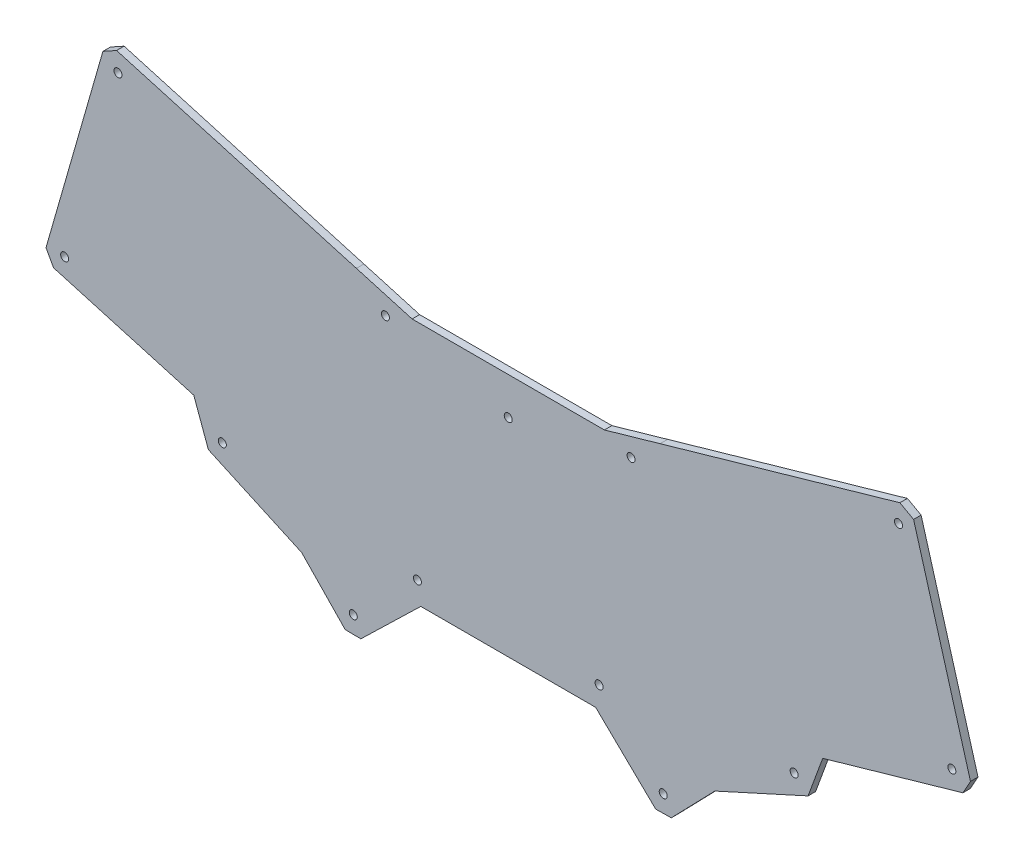
SolidWorks part; units mm, degrees
ref_plane "Plan de face" through (0, 0, 0) normal (0, 0, 1) x (1, 0, 0)
ref_plane "Plan de dessus" through (0, 0, 0) normal (0, 1, 0) x (1, 0, 0)
ref_plane "Plan de droite" through (0, 0, 0) normal (1, 0, 0) x (0, 0, -1)
sketch "Esquisse1" plane through (0, 0, 0) normal (0, 0, 1) x (1, 0, 0)
  line L0 (-121.6461, -32.0475) -> (-108.1875, -28.1884) construction
  line L1 (-108.1875, -28.1884) -> (-104.3283, -41.647) construction
  line L2 (-104.3283, -41.647) -> (-117.7869, -45.5062) construction
  line L3 (-117.7869, -45.5062) -> (-121.6461, -32.0475) construction
  line L4 (-100.1763, -37.9855) -> (-104.0355, -24.5269) construction
  line L5 (-104.0355, -24.5269) -> (-90.5769, -20.6677) construction
  line L6 (-90.5769, -20.6677) -> (-86.7177, -34.1263) construction
  line L7 (-86.7177, -34.1263) -> (-100.1763, -37.9855) construction
  line L8 (-82.5657, -30.4649) -> (-86.4249, -17.0063) construction
  line L9 (-86.4249, -17.0063) -> (-72.9663, -13.1471) construction
  line L10 (-72.9663, -13.1471) -> (-69.1071, -26.6057) construction
  line L11 (-69.1071, -26.6057) -> (-82.5657, -30.4649) construction
  line L12 (-63.6458, -27.5106) -> (-67.505, -14.0519) construction
  line L13 (-67.505, -14.0519) -> (-54.0463, -10.1927) construction
  line L14 (-54.0463, -10.1927) -> (-50.1872, -23.6514) construction
  line L15 (-50.1872, -23.6514) -> (-63.6458, -27.5106) construction
  line L16 (-44.0711, -26.8394) -> (-47.9303, -13.3808) construction
  line L17 (-47.9303, -13.3808) -> (-34.4717, -9.5216) construction
  line L18 (-34.4717, -9.5216) -> (-30.6125, -22.9802) construction
  line L19 (-30.6125, -22.9802) -> (-44.0711, -26.8394) construction
  line L20 (-25.8054, -21.6018) -> (-29.6646, -8.1432) construction
  line L21 (-29.6646, -8.1432) -> (-16.206, -4.284) construction
  line L22 (-16.206, -4.284) -> (-12.3468, -17.7426) construction
  line L23 (-12.3468, -17.7426) -> (-25.8054, -21.6018) construction
  line L24 (-116.4086, -50.3128) -> (-102.95, -46.4536) construction
  line L25 (-102.95, -46.4536) -> (-99.0908, -59.9122) construction
  line L26 (-99.0908, -59.9122) -> (-112.5494, -63.7714) construction
  line L27 (-112.5494, -63.7714) -> (-116.4086, -50.3128) construction
  line L28 (-98.798, -42.7922) -> (-85.3394, -38.933) construction
  line L29 (-85.3394, -38.933) -> (-81.4802, -52.3916) construction
  line L30 (-81.4802, -52.3916) -> (-94.9388, -56.2508) construction
  line L31 (-94.9388, -56.2508) -> (-98.798, -42.7922) construction
  line L32 (-81.1874, -35.2715) -> (-67.7288, -31.4123) construction
  line L33 (-67.7288, -31.4123) -> (-63.8696, -44.8709) construction
  line L34 (-63.8696, -44.8709) -> (-77.3282, -48.7301) construction
  line L35 (-77.3282, -48.7301) -> (-81.1874, -35.2715) construction
  line L36 (-62.2675, -32.3172) -> (-48.8089, -28.458) construction
  line L37 (-48.8089, -28.458) -> (-44.9497, -41.9166) construction
  line L38 (-44.9497, -41.9166) -> (-58.4083, -45.7758) construction
  line L39 (-58.4083, -45.7758) -> (-62.2675, -32.3172) construction
  line L40 (-42.6928, -31.646) -> (-29.2342, -27.7869) construction
  line L41 (-29.2342, -27.7869) -> (-25.375, -41.2455) construction
  line L42 (-25.375, -41.2455) -> (-38.8336, -45.1047) construction
  line L43 (-38.8336, -45.1047) -> (-42.6928, -31.646) construction
  line L44 (-24.4271, -26.4084) -> (-10.9685, -22.5492) construction
  line L45 (-10.9685, -22.5492) -> (-7.1093, -36.0078) construction
  line L46 (-7.1093, -36.0078) -> (-20.5679, -39.867) construction
  line L47 (-20.5679, -39.867) -> (-24.4271, -26.4084) construction
  line L48 (-19.1896, -44.6737) -> (-5.731, -40.8145) construction
  line L49 (-5.731, -40.8145) -> (-1.8718, -54.2731) construction
  line L50 (-1.8718, -54.2731) -> (-15.3304, -58.1323) construction
  line L51 (-15.3304, -58.1323) -> (-19.1896, -44.6737) construction
  line L52 (-37.4554, -49.9113) -> (-23.9967, -46.0521) construction
  line L53 (-23.9967, -46.0521) -> (-20.1376, -59.5107) construction
  line L54 (-20.1376, -59.5107) -> (-33.5962, -63.3699) construction
  line L55 (-33.5962, -63.3699) -> (-37.4554, -49.9113) construction
  line L56 (-57.03, -50.5825) -> (-43.5714, -46.7233) construction
  line L57 (-43.5714, -46.7233) -> (-39.7122, -60.1819) construction
  line L58 (-39.7122, -60.1819) -> (-53.1708, -64.0411) construction
  line L59 (-53.1708, -64.0411) -> (-57.03, -50.5825) construction
  line L60 (-75.9499, -53.5368) -> (-62.4913, -49.6776) construction
  line L61 (-62.4913, -49.6776) -> (-58.6321, -63.1362) construction
  line L62 (-58.6321, -63.1362) -> (-72.0908, -66.9954) construction
  line L63 (-72.0908, -66.9954) -> (-75.9499, -53.5368) construction
  line L64 (-93.5605, -61.0574) -> (-80.1019, -57.1982) construction
  line L65 (-80.1019, -57.1982) -> (-76.2427, -70.6569) construction
  line L66 (-76.2427, -70.6569) -> (-89.7013, -74.516) construction
  line L67 (-89.7013, -74.516) -> (-93.5605, -61.0574) construction
  line L68 (-111.1711, -68.5781) -> (-97.7125, -64.7189) construction
  line L69 (-97.7125, -64.7189) -> (-93.8533, -78.1775) construction
  line L70 (-93.8533, -78.1775) -> (-107.3119, -82.0367) construction
  line L71 (-107.3119, -82.0367) -> (-111.1711, -68.5781) construction
  line L72 (-79.0181, -77.3048) -> (-65.5595, -73.4456) construction
  line L73 (-65.5595, -73.4456) -> (-61.7003, -86.9042) construction
  line L74 (-61.7003, -86.9042) -> (-75.1589, -90.7634) construction
  line L75 (-75.1589, -90.7634) -> (-79.0181, -77.3048) construction
  line L76 (-99.4001, -88.1351) -> (-87.3916, -80.9362) construction
  line L77 (-87.3916, -80.9362) -> (-80.1927, -92.9448) construction
  line L78 (-80.1927, -92.9448) -> (-92.2012, -100.1436) construction
  line L79 (-92.2012, -100.1436) -> (-99.4001, -88.1351) construction
  line L80 (-120.0498, -100.4367) -> (-110.317, -90.3719) construction
  line L81 (-110.317, -90.3719) -> (-100.2522, -100.1047) construction
  line L82 (-100.2522, -100.1047) -> (-109.985, -110.1695) construction
  line L83 (-109.985, -110.1695) -> (-120.0498, -100.4367) construction
  line L86 (0.634, -55.7756) -> (-52.9527, -71.1413) construction
  line L89 (-59.2205, -88.2424) -> (-52.9527, -71.1413) construction
  line L96 (-93.4066, -103.0586) -> (-59.4637, -88.3612) construction
  line L97 (-105.418, -115.2057) -> (-93.9754, -103.3509) construction
  line L98 (-126.5332, -96.9919) -> (-107.5003, -115.385) construction
  line L99 (-167.7972, -50.1766) -> (-183.2082, -64.014) construction
  line L100 (-106.3822, -25.4572) -> (-123.6848, -30.4187) construction
  line L101 (-72.1178, -10.6906) -> (-88.4663, -15.3784) construction
  line L102 (-53.2337, -7.6163) -> (-70.5393, -12.5786) construction
  line L103 (-33.6604, -6.9452) -> (-50.9661, -11.9075) construction
  line L104 (-15.3965, -1.7081) -> (-31.745, -6.396) construction
  line L105 (0.5403, -55.2132) -> (-14.6896, -2.0999) construction
  line L106 (-16.199, -60.6113) -> (0.1495, -55.9235) construction
  line L107 (-52.7198, -71.0835) -> (-18.1144, -61.1606) construction
  line L108 (-59.1184, -88.0534) -> (-52.9674, -71.2752) construction
  line L109 (-183.2082, -64.014) -> (-173.1824, -64.9357) construction
  line L113 (-102.2678, -134.438) -> (-84.7238, -116.3191) construction
  line L114 (-84.7238, -116.3191) -> (-47.2969, -99.2981) construction
  line L115 (-47.2969, -99.2981) -> (-41.4917, -83.4594) construction
  line L116 (14.3812, -67.4381) -> (-41.4917, -83.4594) construction
  line L117 (17.8093, -61.2536) -> (-5.1371, 18.7701) construction
  line L122 (-11.3217, 22.1985) -> (-107.4545, -5.3614) construction
  line L129 (-167.7953, -27.6055) -> (-167.7953, -64.7189) construction
  line L130 (-242.0685, -103.8419) -> (-276.37, -88.2424) construction
  line L131 (-229.5108, -116.8112) -> (-242.0685, -103.8419) construction
  line L138 (-208.9328, -96.8551) -> (-229.5108, -116.8112) construction
  line L139 (-225.5107, -79.6567) -> (-208.9328, -96.8551) construction
  line L140 (-109.3352, -134.5492) -> (-102.2678, -134.438) construction
  line L142 (-5.1371, 18.7701) -> (-11.3217, 22.1985) construction
  line L143 (-211.4691, -30.6868) -> (-225.5107, -79.6567) construction
  line L147 (-114.18, -7.2899) -> (-107.4545, -5.3614) construction
  line L148 (-114.18, -7.2899) -> (-123.7936, -10.0465) construction
  line L154 (-4.3102, 15.8863) -> (-127.3606, -19.3904) construction
  line L155 (-131.531, -101.8802) -> (-105.9239, -126.7133) construction
  line L156 (-105.9239, -126.7133) -> (-89.4162, -109.6646) construction
  line L157 (-127.3539, -97.573) -> (-105.9069, -118.3718) construction
  line L158 (-105.9069, -118.3718) -> (-63.5032, -91.2886) construction
  line L159 (-63.5032, -91.2886) -> (-58.4256, -88.9794) construction
  line L160 (-58.4256, -88.9794) -> (-52.1886, -71.9625) construction
  line L161 (1.8709, -56.4612) -> (-52.1886, -71.9625) construction
  line L162 (1.8709, -56.4612) -> (-14.1861, -0.4639) construction
  line L163 (-14.1861, -0.4639) -> (-50.7166, -10.9388) construction
  line L164 (-50.7166, -10.9388) -> (-52.026, -6.3725) construction
  line L165 (-52.026, -6.3725) -> (-70.2913, -11.61) construction
  line L166 (-70.2913, -11.61) -> (-70.911, -9.4488) construction
  line L167 (-70.911, -9.4488) -> (-90.1377, -14.9608) construction
  line L168 (-90.1377, -14.9608) -> (-89.5177, -17.1231) construction
  line L169 (-89.5177, -17.1231) -> (-107.783, -22.3606) construction
  line L170 (-107.783, -22.3606) -> (-107.0938, -24.7639) construction
  line L171 (-107.0938, -24.7639) -> (-125.3583, -30.0011) construction
  line L172 (-125.3583, -30.0011) -> (-111.0411, -79.9324) construction
  line L173 (-110.7998, -78.9627) -> (-127.3777, -96.1611) construction
  line L174 (-89.4162, -109.6646) -> (-53.6562, -93.4017) construction
  line L175 (-53.6562, -93.4017) -> (-47.6042, -76.8897) construction
  line L176 (9.2923, -60.5749) -> (-47.6042, -76.8897) construction
  line L177 (9.2923, -60.5749) -> (-12.0005, 13.6817) construction
  line L178 (-229.7336, -25.4495) -> (-211.4691, -30.6868) construction
  line L179 (-229.0444, -23.0462) -> (-229.7336, -25.4495) construction
  line L180 (-173.1824, -64.9357) -> (-167.7972, -60.1004) construction
  line L181 (-247.3097, -17.8087) -> (-229.0444, -23.0462) construction
  line L185 (17.8093, -61.2536) -> (14.3812, -67.4381) construction
  line L186 (-183.2987, -65.7677) -> (-173.2729, -66.6895) construction
  line L187 (-173.2729, -66.6895) -> (-167.8052, -74.7882) construction
  line L190 (-246.6897, -15.6465) -> (-247.3097, -17.8087) construction
  line L191 (-263.9939, -10.6857) -> (-246.6897, -15.6465) construction
  line L192 (-264.6136, -12.8469) -> (-263.9939, -10.6857) construction
  line L193 (-282.8789, -7.6094) -> (-264.6136, -12.8469) construction
  line L194 (-284.1883, -12.1757) -> (-282.8789, -7.6094) construction
  line L195 (-320.7188, -1.7008) -> (-284.1883, -12.1757) construction
  line L196 (-336.2245, -55.7756) -> (-320.7188, -1.7008) construction
  line L197 (-183.2987, -65.7677) -> (-167.8052, -88.0782) construction
  line L198 (-181.8414, -71.5322) -> (-174.8684, -81.0171) construction
  line L199 (-174.8684, -81.0171) -> (-178.3549, -83.9622) construction
  line L200 (-344.8828, -60.5749) -> (-323.5901, 13.6817) construction
  line L201 (-344.8828, -60.5749) -> (-287.9863, -76.8897) construction
  line L202 (-281.9343, -93.4017) -> (-287.9863, -76.8897) construction
  line L203 (-246.1743, -109.6646) -> (-281.9343, -93.4017) construction
  line L204 (-224.7907, -78.9627) -> (-208.2128, -96.1611) construction
  line L205 (-210.2322, -30.0011) -> (-224.5494, -79.9324) construction
  line L206 (-228.4967, -24.7639) -> (-210.2322, -30.0011) construction
  line L207 (-227.8075, -22.3606) -> (-228.4967, -24.7639) construction
  line L208 (-246.0728, -17.1231) -> (-227.8075, -22.3606) construction
  line L209 (-245.4528, -14.9608) -> (-246.0728, -17.1231) construction
  line L210 (-264.6796, -9.4488) -> (-245.4528, -14.9608) construction
  line L211 (-265.2993, -11.61) -> (-264.6796, -9.4488) construction
  line L212 (-283.5645, -6.3725) -> (-265.2993, -11.61) construction
  line L213 (-284.8739, -10.9388) -> (-283.5645, -6.3725) construction
  line L217 (0.634, -55.7756) -> (-14.8717, -1.7008) construction
  line L220 (-14.8717, -1.7008) -> (-51.4022, -12.1757) construction
  line L221 (-51.4022, -12.1757) -> (-52.7116, -7.6094) construction
  line L222 (-52.7116, -7.6094) -> (-70.9769, -12.8469) construction
  line L223 (-70.9769, -12.8469) -> (-71.5966, -10.6857) construction
  line L224 (-71.5966, -10.6857) -> (-88.9008, -15.6465) construction
  line L225 (-88.9008, -15.6465) -> (-88.2808, -17.8087) construction
  line L226 (-88.2808, -17.8087) -> (-106.5461, -23.0462) construction
  line L227 (-106.5461, -23.0462) -> (-105.8569, -25.4495) construction
  line L228 (-105.8569, -25.4495) -> (-124.1214, -30.6868) construction
  line L231 (-124.1214, -30.6868) -> (-110.0799, -79.6567) construction
  line L232 (-110.0799, -79.6567) -> (-126.6577, -96.8551) construction
  line L233 (-126.6577, -96.8551) -> (-106.0797, -116.8112) construction
  line L234 (-106.0797, -116.8112) -> (-93.522, -103.8419) construction
  line L235 (-93.522, -103.8419) -> (-59.2205, -88.2424) construction
  line L236 (-321.4044, -0.4639) -> (-284.8739, -10.9388) construction
  line L237 (-337.4614, -56.4612) -> (-321.4044, -0.4639) construction
  line L238 (-337.4614, -56.4612) -> (-283.4019, -71.9625) construction
  line L239 (-277.1649, -88.9794) -> (-283.4019, -71.9625) construction
  line L240 (-272.0873, -91.2886) -> (-277.1649, -88.9794) construction
  line L241 (-229.6837, -118.3718) -> (-272.0873, -91.2886) construction
  line L242 (-208.2366, -97.573) -> (-229.6837, -118.3718) construction
  line L243 (-229.6666, -126.7133) -> (-246.1743, -109.6646) construction
  line L244 (-204.0596, -101.8802) -> (-229.6666, -126.7133) construction
  line L245 (-331.2803, 15.8863) -> (-208.2299, -19.3904) construction
  line L246 (-178.3549, -83.9622) -> (-185.8788, -75.0552) construction
  line L247 (-185.8788, -75.0552) -> (-181.8414, -71.5322) construction
  line L248 (-176.7625, -46.6332) -> (-185.5498, -54.5291) construction
  line L249 (-185.5498, -54.5291) -> (-181.1562, -59.4188) construction
  line L250 (-181.1562, -59.4188) -> (-172.3689, -51.5229) construction
  line L251 (-276.4721, -88.0534) -> (-282.6232, -71.2752) construction
  line L252 (-282.8707, -71.0835) -> (-317.4761, -61.1606) construction
  line L253 (-319.3915, -60.6113) -> (-335.74, -55.9235) construction
  line L254 (-336.1309, -55.2132) -> (-320.9009, -2.0999) construction
  line L255 (-320.194, -1.7081) -> (-303.8455, -6.396) construction
  line L256 (-301.9301, -6.9452) -> (-284.6245, -11.9075) construction
  line L257 (-282.3568, -7.6163) -> (-265.0512, -12.5786) construction
  line L258 (-263.4727, -10.6906) -> (-247.1242, -15.3784) construction
  line L259 (-229.2083, -25.4572) -> (-211.9057, -30.4187) construction
  line L260 (-172.3689, -51.5229) -> (-176.7625, -46.6332) construction
  line L261 (-209.0573, -96.9919) -> (-228.0902, -115.385) construction
  line L262 (-230.1725, -115.2057) -> (-241.6151, -103.3509) construction
  line L263 (-242.1839, -103.0586) -> (-276.1268, -88.3612) construction
  line L264 (-276.37, -88.2424) -> (-282.6379, -71.1413) construction
  line L265 (-336.2245, -55.7756) -> (-282.6379, -71.1413) construction
  line L268 (-353.3998, -61.2536) -> (-349.9717, -67.4381) construction
  line L274 (-221.4105, -7.2899) -> (-206.0252, -11.7015) construction
  line L275 (-221.4105, -7.2899) -> (-228.136, -5.3614) construction
  line L276 (-330.4534, 18.7701) -> (-324.2688, 22.1985) construction
  line L277 (-226.2553, -134.5492) -> (-233.3227, -134.438) construction
  line L281 (-324.2688, 22.1985) -> (-228.136, -5.3614) construction
  line L282 (-353.3998, -61.2536) -> (-330.4534, 18.7701) construction
  line L283 (-349.9717, -67.4381) -> (-294.0988, -83.4594) construction
  line L284 (-288.2936, -99.2981) -> (-294.0988, -83.4594) construction
  line L285 (-250.8667, -116.3191) -> (-288.2936, -99.2981) construction
  line L286 (-233.3227, -134.438) -> (-250.8667, -116.3191) construction
  line L288 (-225.6055, -110.1695) -> (-215.5407, -100.4367) construction
  line L289 (-235.3383, -100.1047) -> (-225.6055, -110.1695) construction
  line L290 (-225.2735, -90.3719) -> (-235.3383, -100.1047) construction
  line L291 (-215.5407, -100.4367) -> (-225.2735, -90.3719) construction
  line L292 (-243.3893, -100.1436) -> (-236.1904, -88.1351) construction
  line L293 (-255.3978, -92.9448) -> (-243.3893, -100.1436) construction
  line L294 (-248.1989, -80.9362) -> (-255.3978, -92.9448) construction
  line L295 (-236.1904, -88.1351) -> (-248.1989, -80.9362) construction
  line L296 (-260.4316, -90.7634) -> (-256.5724, -77.3048) construction
  line L297 (-273.8902, -86.9042) -> (-260.4316, -90.7634) construction
  line L298 (-270.031, -73.4456) -> (-273.8902, -86.9042) construction
  line L299 (-256.5724, -77.3048) -> (-270.031, -73.4456) construction
  line L300 (-228.2786, -82.0367) -> (-224.4194, -68.5781) construction
  line L301 (-241.7372, -78.1775) -> (-228.2786, -82.0367) construction
  line L302 (-237.878, -64.7189) -> (-241.7372, -78.1775) construction
  line L303 (-224.4194, -68.5781) -> (-237.878, -64.7189) construction
  line L304 (-245.8892, -74.516) -> (-242.03, -61.0574) construction
  line L305 (-259.3478, -70.6569) -> (-245.8892, -74.516) construction
  line L306 (-255.4886, -57.1982) -> (-259.3478, -70.6569) construction
  line L307 (-242.03, -61.0574) -> (-255.4886, -57.1982) construction
  line L308 (-263.4998, -66.9954) -> (-259.6406, -53.5368) construction
  line L309 (-276.9584, -63.1362) -> (-263.4998, -66.9954) construction
  line L310 (-273.0992, -49.6776) -> (-276.9584, -63.1362) construction
  line L311 (-259.6406, -53.5368) -> (-273.0992, -49.6776) construction
  line L312 (-282.4197, -64.0411) -> (-278.5605, -50.5825) construction
  line L313 (-295.8783, -60.1819) -> (-282.4197, -64.0411) construction
  line L314 (-292.0191, -46.7233) -> (-295.8783, -60.1819) construction
  line L315 (-278.5605, -50.5825) -> (-292.0191, -46.7233) construction
  line L316 (-301.9944, -63.3699) -> (-298.1352, -49.9113) construction
  line L317 (-315.453, -59.5107) -> (-301.9944, -63.3699) construction
  line L318 (-311.5938, -46.0521) -> (-315.453, -59.5107) construction
  line L319 (-298.1352, -49.9113) -> (-311.5938, -46.0521) construction
  line L320 (-320.2601, -58.1323) -> (-316.4009, -44.6737) construction
  line L321 (-333.7187, -54.2731) -> (-320.2601, -58.1323) construction
  line L322 (-329.8595, -40.8145) -> (-333.7187, -54.2731) construction
  line L323 (-316.4009, -44.6737) -> (-329.8595, -40.8145) construction
  line L324 (-315.0226, -39.867) -> (-311.1634, -26.4084) construction
  line L325 (-328.4812, -36.0078) -> (-315.0226, -39.867) construction
  line L326 (-324.622, -22.5492) -> (-328.4812, -36.0078) construction
  line L327 (-311.1634, -26.4084) -> (-324.622, -22.5492) construction
  line L328 (-296.7569, -45.1047) -> (-292.8977, -31.646) construction
  line L329 (-310.2155, -41.2455) -> (-296.7569, -45.1047) construction
  line L330 (-306.3563, -27.7869) -> (-310.2155, -41.2455) construction
  line L331 (-292.8977, -31.646) -> (-306.3563, -27.7869) construction
  line L332 (-277.1822, -45.7758) -> (-273.323, -32.3172) construction
  line L333 (-290.6408, -41.9166) -> (-277.1822, -45.7758) construction
  line L334 (-286.7817, -28.458) -> (-290.6408, -41.9166) construction
  line L335 (-273.323, -32.3172) -> (-286.7817, -28.458) construction
  line L336 (-258.2623, -48.7301) -> (-254.4031, -35.2715) construction
  line L337 (-271.7209, -44.8709) -> (-258.2623, -48.7301) construction
  line L338 (-267.8617, -31.4123) -> (-271.7209, -44.8709) construction
  line L339 (-254.4031, -35.2715) -> (-267.8617, -31.4123) construction
  line L340 (-240.6517, -56.2508) -> (-236.7925, -42.7922) construction
  line L341 (-254.1103, -52.3916) -> (-240.6517, -56.2508) construction
  line L342 (-250.2511, -38.933) -> (-254.1103, -52.3916) construction
  line L343 (-236.7925, -42.7922) -> (-250.2511, -38.933) construction
  line L344 (-223.0411, -63.7714) -> (-219.1819, -50.3128) construction
  line L345 (-236.4997, -59.9122) -> (-223.0411, -63.7714) construction
  line L346 (-232.6405, -46.4536) -> (-236.4997, -59.9122) construction
  line L347 (-219.1819, -50.3128) -> (-232.6405, -46.4536) construction
  line L348 (-323.2438, -17.7426) -> (-309.7851, -21.6018) construction
  line L349 (-319.3846, -4.284) -> (-323.2438, -17.7426) construction
  line L350 (-305.926, -8.1432) -> (-319.3846, -4.284) construction
  line L351 (-309.7851, -21.6018) -> (-305.926, -8.1432) construction
  line L352 (-304.978, -22.9802) -> (-291.5194, -26.8394) construction
  line L353 (-301.1188, -9.5216) -> (-304.978, -22.9802) construction
  line L354 (-287.6602, -13.3808) -> (-301.1188, -9.5216) construction
  line L355 (-291.5194, -26.8394) -> (-287.6602, -13.3808) construction
  line L356 (-285.4034, -23.6514) -> (-271.9448, -27.5106) construction
  line L357 (-281.5442, -10.1927) -> (-285.4034, -23.6514) construction
  line L358 (-268.0856, -14.0519) -> (-281.5442, -10.1927) construction
  line L359 (-271.9448, -27.5106) -> (-268.0856, -14.0519) construction
  line L360 (-266.4834, -26.6057) -> (-253.0248, -30.4649) construction
  line L361 (-262.6242, -13.1471) -> (-266.4834, -26.6057) construction
  line L362 (-249.1656, -17.0063) -> (-262.6242, -13.1471) construction
  line L363 (-253.0248, -30.4649) -> (-249.1656, -17.0063) construction
  line L364 (-248.8728, -34.1263) -> (-235.4142, -37.9855) construction
  line L365 (-245.0136, -20.6677) -> (-248.8728, -34.1263) construction
  line L366 (-231.555, -24.5269) -> (-245.0136, -20.6677) construction
  line L367 (-235.4142, -37.9855) -> (-231.555, -24.5269) construction
  line L368 (-217.8036, -45.5062) -> (-213.9444, -32.0475) construction
  line L369 (-231.2622, -41.647) -> (-217.8036, -45.5062) construction
  line L370 (-227.4031, -28.1884) -> (-231.2622, -41.647) construction
  line L371 (-213.9444, -32.0475) -> (-227.4031, -28.1884) construction
  line L372 (-226.2553, -134.5492) -> (-194.0347, -103.3509) construction
  line L373 (-109.3352, -134.5492) -> (-141.5559, -103.3509) construction
  line L374 (-141.5559, -103.3509) -> (-194.0347, -103.3509) construction
  line L375 (-167.7972, -50.1766) -> (-152.3861, -64.014) construction
  line L376 (-162.4119, -64.9357) -> (-167.7972, -60.1004) construction
  line L377 (-162.3376, -66.6895) -> (-167.8052, -74.7882) construction
  line L378 (-152.3118, -65.7677) -> (-167.8052, -88.0782) construction
  line L379 (-163.2254, -51.5229) -> (-158.8318, -46.6332) construction
  line L380 (-154.4381, -59.4188) -> (-163.2254, -51.5229) construction
  line L381 (-150.0445, -54.5291) -> (-154.4381, -59.4188) construction
  line L382 (-158.8318, -46.6332) -> (-150.0445, -54.5291) construction
  line L383 (-149.7316, -75.0552) -> (-153.7691, -71.5322) construction
  line L384 (-157.2555, -83.9622) -> (-149.7316, -75.0552) construction
  line L385 (-160.742, -81.0171) -> (-157.2555, -83.9622) construction
  line L386 (-153.7691, -71.5322) -> (-160.742, -81.0171) construction
  line L387 (-152.3118, -65.7677) -> (-162.3376, -66.6895) construction
  line L388 (-152.3861, -64.014) -> (-162.4119, -64.9357) construction
  line L389 (-206.0252, -11.7015) -> (-129.5654, -11.7015) construction
  line L390 (-119.0708, -62.7964) -> (-130.6498, -22.4155) construction
  line L391 (-123.5545, -47.16) -> (-127.4136, -33.7014) construction
  line L392 (-120.442, -65.2702) -> (-138.2688, -70.3819) construction
  line L393 (-140.7426, -69.0107) -> (-154.4194, -21.3141) construction
  line L394 (-167.1758, -11.7015) -> (-206.0252, -11.7015) construction
  line L395 (-156.8153, -19.5087) -> (-167.1758, -11.7015) construction
  line L396 (-123.7936, -10.0465) -> (-130.6498, -22.4155) construction
  line L397 (-138.2688, -70.3819) -> (-140.7426, -69.0107) construction
  line L398 (-119.0708, -62.7964) -> (-120.442, -65.2702) construction
  line L399 (-129.5654, -11.7015) -> (-123.7936, -10.0465) construction
  line L400 (-207.5404, -98.2908) -> (-228.1196, -118.248) construction
  line L401 (-231.2409, -118.5638) -> (-272.5658, -92.1695) construction
  line L402 (-272.5658, -92.1695) -> (-277.9598, -89.7165) construction
  line L403 (-277.9598, -89.7165) -> (-284.166, -72.7837) construction
  line L404 (-336.7758, -57.6981) -> (-284.166, -72.7837) construction
  line L405 (-338.147, -55.2243) -> (-320.7131, 5.5749) construction
  line L406 (-223.5881, -80.208) -> (-202.439, -93.7159) construction
  line L407 (-202.439, -93.7159) -> (-207.5404, -98.2908) construction
  line L408 (-17.3512, 6.9463) -> (-127.905, -24.7479) construction
  line L409 (2.5565, -55.2243) -> (-14.8774, 5.5749) construction
  line L410 (-318.2393, 6.9463) -> (-167.7953, -36.1838) construction
  line L411 (1.1853, -57.6981) -> (-51.4245, -72.7837) construction
  line L412 (-57.6307, -89.7165) -> (-51.4245, -72.7837) construction
  line L413 (-63.0247, -92.1695) -> (-57.6307, -89.7165) construction
  line L414 (-104.3497, -118.5638) -> (-63.0247, -92.1695) construction
  line L415 (-207.6856, -24.7479) -> (-223.5881, -80.208) construction
  line L416 (-338.6983, -57.1468) -> (-322.0901, 0.773) construction
  line L417 (-265.3652, -8.212) -> (-244.2159, -14.2752) construction
  line L418 (-208.9953, -29.3155) -> (-223.5881, -80.208) construction
  line L419 (-227.2598, -24.0783) -> (-208.9953, -29.3155) construction
  line L420 (-226.5706, -21.6749) -> (-227.2598, -24.0783) construction
  line L421 (-244.8359, -16.4375) -> (-226.5706, -21.6749) construction
  line L422 (-244.2159, -14.2752) -> (-244.8359, -16.4375) construction
  line L423 (-265.9849, -10.3731) -> (-265.3652, -8.212) construction
  line L424 (-284.2502, -5.1356) -> (-265.9849, -10.3731) construction
  line L425 (-285.5595, -9.7019) -> (-284.2502, -5.1356) construction
  line L426 (-322.0901, 0.773) -> (-285.5595, -9.7019) construction
  line L427 (-128.0501, -98.2908) -> (-107.4709, -118.248) construction
  line L428 (-133.1515, -93.7159) -> (-128.0501, -98.2908) construction
  line L429 (-127.905, -24.7479) -> (-167.7953, -36.1862) construction
  line L430 (-129.8233, -25.2979) -> (-130.6498, -22.4155) construction
  line L431 (-202.439, -93.7159) -> (-133.1515, -93.7159) construction
  line L432 (-167.7953, -36.1838) -> (-156.4257, -23.5445) construction
  line L433 (-129.8233, -25.2979) -> (-127.905, -24.7479) construction
  line L434 (-156.4257, -23.5445) -> (-156.8153, -19.5087) construction
  line L435 (-320.7131, 5.5749) -> (-318.2393, 6.9463) construction
  line L436 (-338.6983, -57.1468) -> (-284.166, -72.7837) construction
  line L437 (-338.147, -55.2243) -> (-336.7758, -57.6981) construction
  line L438 (-207.5404, -98.2908) -> (-229.5553, -119.6404) construction
  line L439 (-229.5553, -119.6404) -> (-272.5658, -92.1695) construction
  line L440 (-228.1196, -118.248) -> (-231.2409, -118.5638) construction
  line L441 (-107.4709, -118.248) -> (-104.3497, -118.5638) construction
  line L442 (2.5565, -55.2243) -> (1.1853, -57.6981) construction
  line L443 (-14.8774, 5.5749) -> (-17.3512, 6.9463) construction
  line L444 (-167.1758, -11.7015) -> (-129.5654, -11.7015) construction
  line L445 (-214.6968, -14.5277) -> (-217.8401, -13.8763) construction
  line L446 (-217.8401, -13.8763) -> (-219.9759, -16.2728) construction
  line L447 (-219.9759, -16.2728) -> (-218.9683, -19.3206) construction
  line L448 (-218.9683, -19.3206) -> (-215.8251, -19.972) construction
  line L449 (-215.8251, -19.972) -> (-213.6893, -17.5755) construction
  line L450 (-213.6893, -17.5755) -> (-214.6968, -14.5277) construction
  line L451 (-166.1757, -24.834) -> (-169.3858, -24.8172) construction
  line L452 (-169.3858, -24.8172) -> (-171.0053, -27.5888) construction
  line L453 (-171.0053, -27.5888) -> (-169.4148, -30.3771) construction
  line L454 (-169.4148, -30.3771) -> (-166.2047, -30.3939) construction
  line L455 (-166.2047, -30.3939) -> (-164.5852, -27.6223) construction
  line L456 (-164.5852, -27.6223) -> (-166.1757, -24.834) construction
  line L457 (-115.6722, -16.0395) -> (-117.9812, -13.8095) construction
  line L458 (-117.9812, -13.8095) -> (-121.0669, -14.6941) construction
  line L459 (-121.0669, -14.6941) -> (-121.8437, -17.8088) construction
  line L460 (-121.8437, -17.8088) -> (-119.5347, -20.0388) construction
  line L461 (-119.5347, -20.0388) -> (-116.4489, -19.1542) construction
  line L462 (-116.4489, -19.1542) -> (-115.6722, -16.0395) construction
  line L463 (-9.2401, 15.3202) -> (-12.0393, 16.8915) construction
  line L464 (-12.0393, 16.8915) -> (-14.7996, 15.253) construction
  line L465 (-14.7996, 15.253) -> (-14.7608, 12.0431) construction
  line L466 (-14.7608, 12.0431) -> (-11.9616, 10.4718) construction
  line L467 (-11.9616, 10.4718) -> (-9.2013, 12.1103) construction
  line L468 (-9.2013, 12.1103) -> (-9.2401, 15.3202) construction
  line L469 (12.5024, -60.5749) -> (10.8973, -57.7949) construction
  line L470 (10.8973, -57.7949) -> (7.6873, -57.7949) construction
  line L471 (7.6873, -57.7949) -> (6.0822, -60.5749) construction
  line L472 (6.0822, -60.5749) -> (7.6873, -63.3549) construction
  line L473 (7.6873, -63.3549) -> (10.8973, -63.3549) construction
  line L474 (10.8973, -63.3549) -> (12.5024, -60.5749) construction
  line L475 (-50.6498, -94.5269) -> (-51.1786, -91.3606) construction
  line L476 (-51.1786, -91.3606) -> (-54.185, -90.2355) construction
  line L477 (-54.185, -90.2355) -> (-56.6626, -92.2765) construction
  line L478 (-56.6626, -92.2765) -> (-56.1338, -95.4427) construction
  line L479 (-56.1338, -95.4427) -> (-53.1274, -96.5679) construction
  line L480 (-53.1274, -96.5679) -> (-50.6498, -94.5269) construction
  line L481 (-104.4402, -129.5599) -> (-102.7168, -126.8517) construction
  line L482 (-102.7168, -126.8517) -> (-104.2006, -124.0051) construction
  line L483 (-104.2006, -124.0051) -> (-107.4076, -123.8667) construction
  line L484 (-107.4076, -123.8667) -> (-109.131, -126.575) construction
  line L485 (-109.131, -126.575) -> (-107.6473, -129.4216) construction
  line L486 (-107.6473, -129.4216) -> (-104.4402, -129.5599) construction
  line L487 (-132.1348, -105.033) -> (-129.1025, -103.9795) construction
  line L488 (-129.1025, -103.9795) -> (-128.4987, -100.8268) construction
  line L489 (-128.4987, -100.8268) -> (-130.9271, -98.7274) construction
  line L490 (-130.9271, -98.7274) -> (-133.9594, -99.7809) construction
  line L491 (-133.9594, -99.7809) -> (-134.5633, -102.9336) construction
  line L492 (-134.5633, -102.9336) -> (-132.1348, -105.033) construction
  line L493 (-200.9863, -102.8073) -> (-201.7201, -99.6822) construction
  line L494 (-201.7201, -99.6822) -> (-204.7933, -98.7551) construction
  line L495 (-204.7933, -98.7551) -> (-207.1328, -100.9531) construction
  line L496 (-207.1328, -100.9531) -> (-206.3991, -104.0782) construction
  line L497 (-206.3991, -104.0782) -> (-203.3258, -105.0053) construction
  line L498 (-203.3258, -105.0053) -> (-200.9863, -102.8073) construction
  line L499 (-228.0726, -129.4997) -> (-226.4565, -126.726) construction
  line L500 (-226.4565, -126.726) -> (-228.0506, -123.9397) construction
  line L501 (-228.0506, -123.9397) -> (-231.2606, -123.927) construction
  line L502 (-231.2606, -123.927) -> (-232.8766, -126.7006) construction
  line L503 (-232.8766, -126.7006) -> (-231.2826, -129.4869) construction
  line L504 (-231.2826, -129.4869) -> (-228.0726, -129.4997) construction
  line L505 (-279.7615, -95.7646) -> (-278.8016, -92.7014) construction
  line L506 (-278.8016, -92.7014) -> (-280.9744, -90.3385) construction
  line L507 (-280.9744, -90.3385) -> (-284.1072, -91.0388) construction
  line L508 (-284.1072, -91.0388) -> (-285.0671, -94.102) construction
  line L509 (-285.0671, -94.102) -> (-282.8943, -96.4649) construction
  line L510 (-282.8943, -96.4649) -> (-279.7615, -95.7646) construction
  line L511 (-343.3818, -63.4124) -> (-341.6749, -60.6938) construction
  line L512 (-341.6749, -60.6938) -> (-343.176, -57.8563) construction
  line L513 (-343.176, -57.8563) -> (-346.3838, -57.7374) construction
  line L514 (-346.3838, -57.7374) -> (-348.0907, -60.4561) construction
  line L515 (-348.0907, -60.4561) -> (-346.5896, -63.2936) construction
  line L516 (-346.5896, -63.2936) -> (-343.3818, -63.4124) construction
  line L517 (-323.3776, 16.8847) -> (-326.2578, 15.4671) construction
  line L518 (-326.2578, 15.4671) -> (-326.4702, 12.2641) construction
  line L519 (-326.4702, 12.2641) -> (-323.8025, 10.4786) construction
  line L520 (-323.8025, 10.4786) -> (-320.9224, 11.8962) construction
  line L521 (-320.9224, 11.8962) -> (-320.7099, 15.0992) construction
  line L522 (-320.7099, 15.0992) -> (-323.3776, 16.8847) construction
  line L523 (-129.5654, -11.7015) -> (-123.7936, -10.0465) construction
  line L524 (-324.1462, 21.1231) -> (-228.4116, -6.3226)
  line L525 (-221.6861, -8.2511) -> (-228.4116, -6.3226)
  line L526 (-221.6861, -8.2511) -> (-206.1657, -12.7015)
  line L527 (-167.1758, -12.7015) -> (-206.1657, -12.7015)
  line L528 (-167.1758, -12.7015) -> (-129.4248, -12.7015)
  line L529 (-129.4248, -12.7015) -> (-123.5179, -11.0078)
  line L530 (-113.9044, -8.2511) -> (-123.5179, -11.0078)
  line L531 (-113.9044, -8.2511) -> (-107.1789, -6.3226)
  line L532 (-11.4443, 21.1231) -> (-107.1789, -6.3226)
  line L533 (-5.9842, 18.0963) -> (-11.4443, 21.1231)
  line L534 (16.7339, -61.1311) -> (-5.9842, 18.0963)
  line L535 (16.7339, -61.1311) -> (13.7074, -66.591)
  line L536 (13.7074, -66.591) -> (-42.2558, -82.6382)
  line L537 (-48.0918, -98.561) -> (-42.2558, -82.6382)
  line L538 (-85.3104, -115.4872) -> (-48.0918, -98.561)
  line L539 (-102.6979, -133.4446) -> (-85.3104, -115.4872)
  line L540 (-108.937, -133.5428) -> (-102.6979, -133.4446)
  line L541 (-108.937, -133.5428) -> (-132.8889, -110.3509)
  line L542 (-141.1511, -102.3509) -> (-194.4395, -102.3509) construction
  line L543 (-226.6535, -133.5428) -> (-202.7016, -110.3509)
  line L544 (-226.6535, -133.5428) -> (-232.8926, -133.4446)
  line L545 (-232.8926, -133.4446) -> (-250.2802, -115.4872)
  line L546 (-250.2802, -115.4872) -> (-287.4987, -98.561)
  line L547 (-287.4987, -98.561) -> (-293.3347, -82.6382)
  line L548 (-349.2979, -66.591) -> (-293.3347, -82.6382)
  line L549 (-352.3244, -61.1311) -> (-349.2979, -66.591)
  line L550 (-352.3244, -61.1311) -> (-329.6063, 18.0963)
  line L551 (-329.6063, 18.0963) -> (-324.1462, 21.1231)
  line L552 (-132.8889, -110.3509) -> (-202.7016, -110.3509)
  line L553 (-141.1511, -110.3509) -> (-194.4395, -110.3509) construction
  line L555 (-226.6535, -133.5428) -> (-194.4395, -102.3509) construction
  line L556 (-108.937, -133.5428) -> (-141.1511, -102.3509) construction
  circle A2 centre (-12.0005, 13.6817) radius 1.6
  circle A3 centre (-12.0005, 13.6817) radius 3 construction
  circle A4 centre (-118.7579, -16.9241) radius 1.6
  circle A5 centre (9.2923, -60.5749) radius 1.6
  circle A6 centre (-53.6562, -93.4017) radius 1.6
  circle A7 centre (-105.9239, -126.7133) radius 1.6
  circle A8 centre (-131.531, -101.8802) radius 1.6
  circle A10 centre (-147.4897, -45.973) radius 1.6 construction
  circle A11 centre (-323.5901, 13.6817) radius 3 construction
  circle A12 centre (-188.1008, -45.973) radius 1.6 construction
  circle A14 centre (-204.0596, -101.8802) radius 1.6
  circle A15 centre (-229.6666, -126.7133) radius 1.6
  circle A16 centre (-281.9343, -93.4017) radius 1.6
  circle A17 centre (-344.8828, -60.5749) radius 1.6
  circle A18 centre (-216.8326, -16.9241) radius 1.6
  circle A19 centre (-323.5901, 13.6817) radius 1.6
  circle A20 centre (-167.7953, -27.6055) radius 1.6
  circle A21 centre (-216.8326, -16.9241) radius 2.78 construction
  circle A22 centre (-167.7953, -27.6055) radius 2.78 construction
  circle A23 centre (-118.7579, -16.9241) radius 2.78 construction
  circle A24 centre (-12.0005, 13.6817) radius 2.78 construction
  circle A25 centre (9.2923, -60.5749) radius 2.78 construction
  circle A26 centre (-53.6562, -93.4017) radius 2.78 construction
  circle A27 centre (-105.9239, -126.7133) radius 2.78 construction
  circle A28 centre (-131.531, -101.8802) radius 2.78 construction
  circle A29 centre (-204.0596, -101.8802) radius 2.78 construction
  circle A30 centre (-229.6666, -126.7133) radius 2.78 construction
  circle A31 centre (-281.9343, -93.4017) radius 2.78 construction
  circle A32 centre (-344.8828, -60.5749) radius 2.78 construction
  circle A33 centre (-323.5901, 13.6817) radius 2.78 construction
  point P138 (-167.7953, -27.6055)
  point P139 (-6.5153, 23.5764)
  point P150 (-169.1046, -23.0392)
  point P200 (19.1875, -66.0599)
  point P203 (-141.5228, -71.3355)
  point P204 (-141.5228, 1.5705)
  point P263 (-133.4062, -12.8029)
  point P264 (-118.5195, -64.7189)
  point P283 (-140.1914, -70.9332)
  point P284 (-157.1758, -11.7015)
  point P405 (-354.778, -66.0599)
  point P406 (-329.0752, 23.5764)
  point P423 (-15.4286, 7.4974)
  point P424 (-320.1619, 7.4974)
  point P429 (3.1078, -57.1468)
  point P434 (-106.0352, -119.6404)
  dimension "D3" = 3.2
  dimension "D4" = 6
  dimension "D6" = 3.2
  dimension "D7" = 3.2
  dimension "D8" = 3.2
  dimension "D9" = 3.2
  dimension "D10" = 3.2
  dimension "D16" = 3.2
  dimension "D21" = 5.56
  dimension "D34" = 5.56
  dimension "D2" = 6
  dimension "D5" = 1
  dimension "D11" = 5.56
  dimension "D14" = 5.56
  dimension "D22" = 5.56
  dimension "D26" = 5.56
  dimension "D27" = 5.56
  dimension "D28" = 5.56
  dimension "D29" = 5.56
  dimension "D30" = 5.56
  dimension "D31" = 5.56
  dimension "D32" = 5.56
  dimension "D33" = 5.56
  dimension "D35" = 1
  dimension "D36" = 8
extrude "Boss.-Extru.1" add sketch "Esquisse1" along normal blind 3
